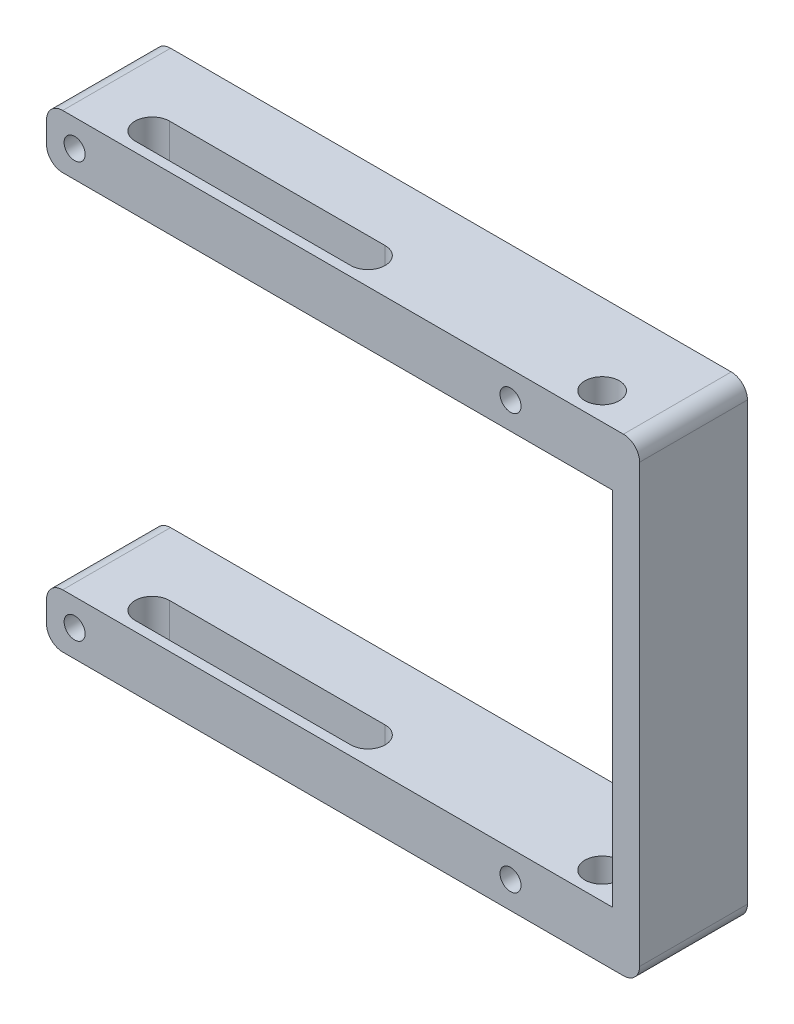
SolidWorks part; units mm, degrees
ref_plane "Alzado" through (0, 0, 0) normal (0, 0, 1) x (1, 0, 0)
ref_plane "Planta" through (0, 0, 0) normal (0, 1, 0) x (1, 0, 0)
ref_plane "Vista lateral" through (0, 0, 0) normal (1, 0, 0) x (0, 0, -1)
sketch "Croquis1" plane through (0, 0, 0) normal (0, 0, 1) x (1, 0, 0)
  line L0 (71.8143, 48.5) -> (-71.8143, 48.5) construction
  line L1 (67.8143, 5) -> (-42.1857, 5)
  line L2 (67.8143, 5) -> (67.8143, 15)
  line L3 (67.8143, 15) -> (-42.1857, 15)
  line L4 (-42.1857, 5) -> (-42.1857, 15)
  line L5 (-42.1857, 92) -> (-42.1857, 82)
  line L6 (67.8143, 92) -> (-42.1857, 92)
  line L7 (67.8143, 82) -> (-42.1857, 82)
  line L8 (67.8143, 92) -> (67.8143, 82)
  line L10 (67.8143, 92) -> (62.8143, 92)
  line L11 (67.8143, 92) -> (67.8143, 5)
  line L12 (67.8143, 5) -> (62.8143, 5)
  line L13 (62.8143, 92) -> (62.8143, 5)
  dimension "D1" = 10
  dimension "D2" = 110
  dimension "D3" = 5
extrude "Saliente-Extruir1" add sketch "Croquis1" along normal blind 10 contours L13 L6 L5 L7 | L6 L13 L7 L8 | L0 L11 L7 L13 | L11 L0 L13 L3 | L3 L13 L1 L2 | L13 L3 L4 L1
sketch "Croquis2" plane through (0, 92, 0) normal (0, 1, 0) x (1, 0, 0)
  line L0 (67.8143, -5) -> (-42.1857, -5) construction
  line L1 (67.8143, -10) -> (67.8143, 0) construction
  line L2 (-42.1857, -10) -> (-42.1857, 0) construction
  line L3 (12.4257, -5) -> (-27.5743, -5) construction
  line L4 (12.4257, -8.2) -> (-27.5743, -8.2)
  line L5 (12.4257, -1.8) -> (-27.5743, -1.8)
  circle A0 centre (55.8605, -5) radius 3.2
  arc A1 (12.4257, -8.2) -> (12.4257, -1.8) centre (12.4257, -5) ccw
  arc A2 (-27.5743, -1.8) -> (-27.5743, -8.2) centre (-27.5743, -5) ccw
  point P10 (-7.5743, -5)
  dimension "D1" = 6.4
  dimension "D2" = 40
  dimension "D3" = 6.4
extrude "Cortar-Extruir1" cut sketch "Croquis2" against normal through all
sketch "Croquis3" plane through (0, 0, 10) normal (0, 0, 1) x (1, 0, 0)
  line L0 (-42.1857, 87) -> (67.8143, 87) construction
  line L1 (-42.1857, 92) -> (-42.1857, 82) construction
  line L2 (67.8143, 92) -> (67.8143, 5) construction
  line L3 (-42.1857, 10) -> (67.8143, 10) construction
  line L4 (-42.1857, 5) -> (-42.1857, 15) construction
  line L5 (-36.9798, 92) -> (-36.9798, 5) construction
  line L6 (67.8143, 92) -> (-42.1857, 92) construction
  line L7 (67.8143, 5) -> (-42.1857, 5) construction
  line L8 (43.8693, 5) -> (43.8693, 92) construction
  circle A0 centre (-36.9798, 87) radius 1.95
  circle A1 centre (-36.9798, 10) radius 1.95
  circle A2 centre (43.8693, 10) radius 1.95
  circle A3 centre (43.8693, 87) radius 1.95
  dimension "D1" = 3.9
  dimension "D2" = 3.9
  dimension "D3" = 3.9
  dimension "D4" = 3.9
extrude "Cortar-Extruir2" cut sketch "Croquis3" against normal blind 4.9
sketch "Croquis4" plane through (0, 0, 5.1) normal (0, 0, 1) x (1, 0, 0)
  circle A0 centre (-36.9798, 87) radius 1.65
  circle A1 centre (-36.9798, 10) radius 1.65
  circle A2 centre (43.8693, 10) radius 1.65
  circle A3 centre (43.8693, 87) radius 1.65
  dimension "D1" = 3.3
  dimension "D2" = 3.3
  dimension "D3" = 3.3
  dimension "D4" = 3.3
extrude "Cortar-Extruir3" cut sketch "Croquis4" against normal through all
fillet "Redondeo1" radius 3 6 edges at (67.8143, 92, 5) (67.8143, 5, 5) (-42.1857, 5, 5) (-42.1857, 15, 5) (-42.1857, 92, 5) (-42.1857, 82, 5)
sketch "Croquis7" plane through (0, 0, 0) normal (0, 0, -1) x (-1, 0, 0)
  line L8 (39.1857, 92) -> (-64.8143, 92)
  line L9 (-67.8143, 89) -> (-67.8143, 8)
  line L10 (-64.8143, 5) -> (39.1857, 5)
  line L11 (42.1857, 8) -> (42.1857, 12)
  line L12 (39.1857, 15) -> (-62.8143, 15)
  line L13 (-62.8143, 15) -> (-62.8143, 82)
  line L14 (-62.8143, 82) -> (39.1857, 82)
  line L15 (42.1857, 85) -> (42.1857, 89)
  line L16 (39.1857, 92) -> (-64.8143, 92)
  line L17 (-67.8143, 89) -> (-67.8143, 8)
  line L18 (-64.8143, 5) -> (39.1857, 5)
  line L19 (42.1857, 8) -> (42.1857, 12)
  line L20 (39.1857, 15) -> (-62.8143, 15)
  line L21 (-62.8143, 15) -> (-62.8143, 82)
  line L22 (-62.8143, 82) -> (39.1857, 82)
  line L23 (42.1857, 85) -> (42.1857, 89)
  circle A0 centre (-43.8693, 87) radius 1.65 construction
  circle A1 centre (36.9798, 87) radius 1.65 construction
  circle A2 centre (36.9798, 10) radius 1.65 construction
  circle A3 centre (-43.8693, 10) radius 1.65 construction
  circle A4 centre (36.9798, 87) radius 1.65
  circle A5 centre (36.9798, 10) radius 1.65
  arc A6 (-64.8143, 92) -> (-67.8143, 89) centre (-64.8143, 89) ccw
  arc A7 (-67.8143, 8) -> (-64.8143, 5) centre (-64.8143, 8) ccw
  arc A8 (39.1857, 5) -> (42.1857, 8) centre (39.1857, 8) ccw
  arc A9 (42.1857, 12) -> (39.1857, 15) centre (39.1857, 12) ccw
  arc A10 (39.1857, 82) -> (42.1857, 85) centre (39.1857, 85) ccw
  arc A11 (42.1857, 89) -> (39.1857, 92) centre (39.1857, 89) ccw
  arc A12 (-64.8143, 92) -> (-67.8143, 89) centre (-64.8143, 89) ccw
  arc A13 (-67.8143, 8) -> (-64.8143, 5) centre (-64.8143, 8) ccw
  arc A14 (39.1857, 5) -> (42.1857, 8) centre (39.1857, 8) ccw
  arc A15 (42.1857, 12) -> (39.1857, 15) centre (39.1857, 12) ccw
  arc A16 (39.1857, 82) -> (42.1857, 85) centre (39.1857, 85) ccw
  arc A17 (42.1857, 89) -> (39.1857, 92) centre (39.1857, 89) ccw
  circle A18 centre (-43.8693, 10) radius 1.65
  circle A19 centre (-43.8693, 87) radius 1.65
  dimension "D1" = 0
extrude "Saliente-Extruir2" add sketch "Croquis7" along normal blind 10
